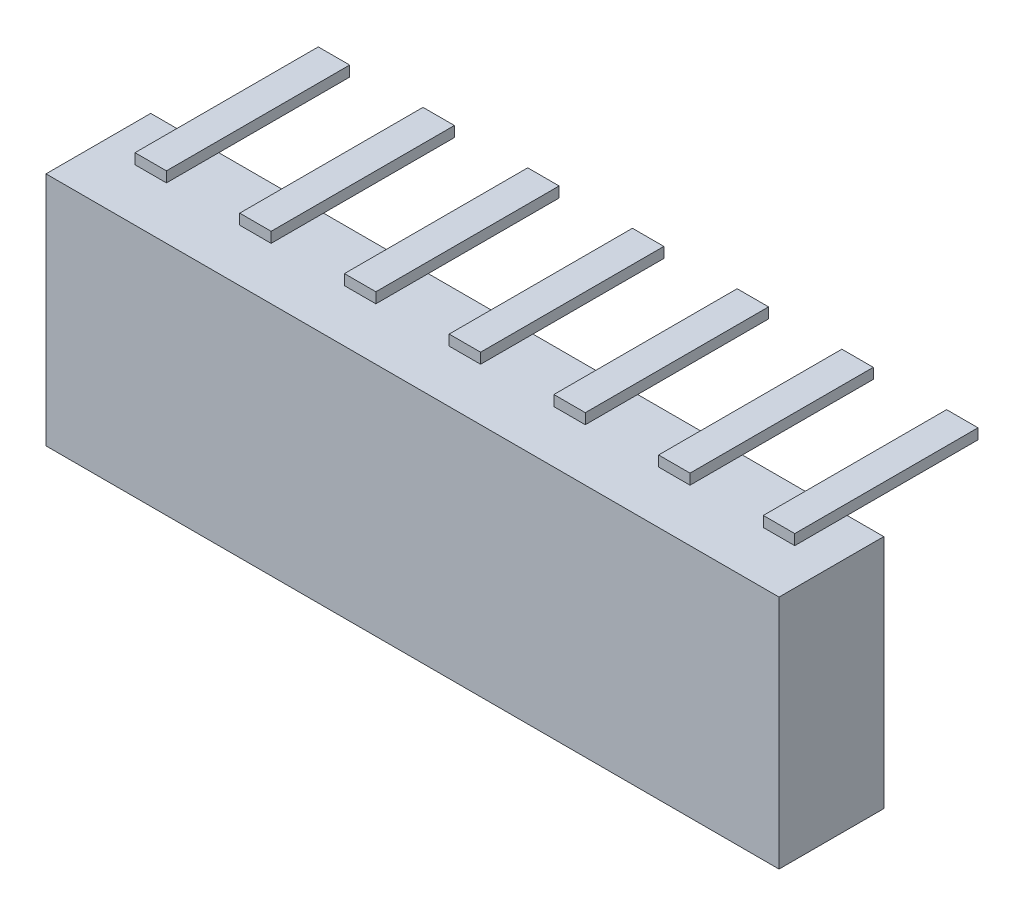
SolidWorks part; units mm, degrees
ref_plane "Front Plane" through (0, 0, 0) normal (0, 0, 1) x (1, 0, 0)
ref_plane "Top Plane" through (0, 0, 0) normal (0, 1, 0) x (1, 0, 0)
ref_plane "Right Plane" through (0, 0, 0) normal (1, 0, 0) x (0, 0, -1)
sketch "Sketch1" plane through (0, 0, 0) normal (0, 0, 1) x (1, 0, 0)
  line L1 (-1, 2.25) -> (1, 2.25)
  line L2 (-1, 2.25) -> (-1, -2.25)
  line L3 (-1, -2.25) -> (1, -2.25)
  line L4 (1, 2.25) -> (1, -2.25)
  line L5 (-1, 2.25) -> (1, -2.25) construction
  line L6 (-1, -2.25) -> (1, 2.25) construction
  point P0 (0, 0)
  dimension "D1" = 2
  dimension "D2" = 4.5
extrude "Boss-Extrude1" add sketch "Sketch1" along normal blind 2
sketch "Sketch2" plane through (0, -2.25, 0) normal (0, -1, 0) x (1, 0, 0)
  line L0 (0, 0) -> (0, 2) construction
  line L1 (-1, 2) -> (1, 2) construction
  line L9 (-0.4, 1.4) -> (0.4, 1.4)
  line L10 (-0.4, 1.4) -> (-0.4, 0.6)
  line L11 (-0.4, 0.6) -> (0.4, 0.6)
  line L12 (0.4, 1.4) -> (0.4, 0.6)
  line L13 (-0.4, 1.4) -> (0.4, 0.6) construction
  line L14 (-0.4, 0.6) -> (0.4, 1.4) construction
  point P10 (0, 1)
  dimension "D1" = 0.8
extrude "Cut-Extrude1" cut sketch "Sketch2" against normal blind 2.8
chamfer "Chamfer1" distance 0.2 angle 45 4 edges at (-0.4, -2.25, 1) (0, -2.25, 0.6) (0.4, -2.25, 1) (0, -2.25, 1.4)
sketch "Sketch3" plane through (0, 0, 0) normal (1, 0, 0) x (0, 0, -1)
  line L0 (-1, 2.25) -> (-1, 2.45)
  line L1 (-2, 2.25) -> (0, 2.25) construction
  line L2 (-1, 2.45) -> (2.5, 2.45)
  line L3 (2.5, 2.45) -> (2.5, 2.25)
  line L4 (2.5, 2.25) -> (-1, 2.25)
  line L5 (0, -2.25) -> (0, 2.25) construction
  dimension "D1" = 0.2
  dimension "D2" = 2.5
extrude "Boss-Extrude2" add sketch "Sketch3" along normal mid plane 0.6
pattern_linear "LPattern1" count 7 spacing 2 along (1, 0, 0) of "Boss-Extrude1", "Cut-Extrude1", "Chamfer1", "Boss-Extrude2"
ref_plane "Plane1" through (6, 0, 0) normal (1, 0, 0) x (0, 0, -1)
